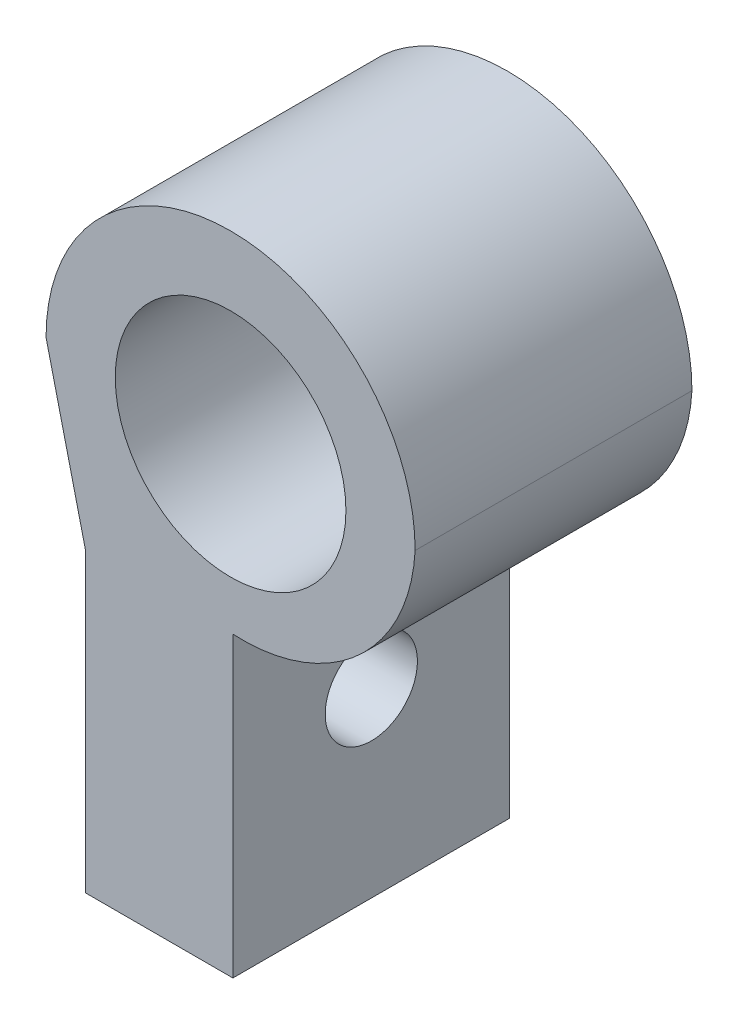
SolidWorks part; units mm, degrees
ref_plane "Alzado" through (0, 0, 0) normal (0, 0, 1) x (1, 0, 0)
ref_plane "Planta" through (0, 0, 0) normal (0, 1, 0) x (1, 0, 0)
ref_plane "Vista lateral" through (0, 0, 0) normal (1, 0, 0) x (0, 0, -1)
sketch "Croquis1" plane through (0, 0, 0) normal (0, 0, 1) x (1, 0, 0)
  line L3 (-3.15, -10) -> (-3.15, -3.5453)
  line L4 (-2.5, 0) -> (-12.65, 0) construction
  line L5 (-3.15, -3.5453) -> (-4, 0)
  line L6 (0.05, -10) -> (0.05, -3.5453)
  line L7 (-3.15, -10) -> (0.05, -10)
  circle A0 centre (0, 0) radius 2.5
  arc A1 (4, 0) -> (-4, 0) centre (0, 0) ccw
  arc A2 (0.05, -3.5453) -> (4, 0) centre (0.2524, 0.2024) ccw
  dimension "D1" = 3.2
  dimension "D2" = 5
  dimension "D3" = 4
  dimension "D4" = 10.15
  dimension "D5" = 9.5
extrude "Saliente-Extruir1" add sketch "Croquis1" along normal blind 6
sketch "Croquis4" plane through (0.05, 0, 0) normal (1, 0, 0) x (0, 0, -1)
  line L0 (-6, -3.5507) -> (0, -3.5507) construction
  circle A0 centre (-3, -6.0507) radius 1
  dimension "D1" = 2.5
extrude "Cortar-Extruir2" cut sketch "Croquis4" against normal up to vertex (3.2 mm away)
